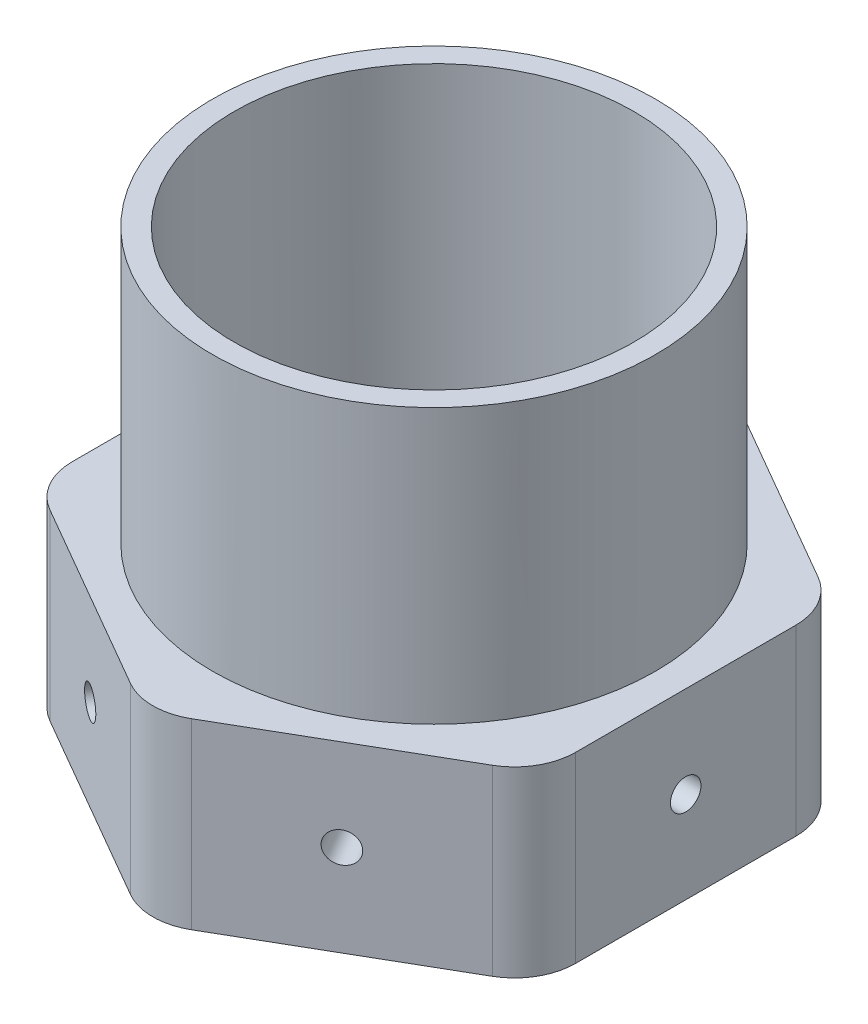
SolidWorks part; units mm, degrees
ref_plane "Front Plane" through (0, 0, 0) normal (0, 0, 1) x (1, 0, 0)
ref_plane "Top Plane" through (0, 0, 0) normal (0, 1, 0) x (1, 0, 0)
ref_plane "Right Plane" through (0, 0, 0) normal (1, 0, 0) x (0, 0, -1)
sketch "Sketch1" plane through (0, 0, 0) normal (0, 1, 0) x (1, 0, 0)
  line L9 (0, -60.5652) -> (52.451, -30.2826)
  line L10 (52.451, -30.2826) -> (52.451, 30.2826)
  line L11 (52.451, 30.2826) -> (0, 60.5652)
  line L12 (0, 60.5652) -> (-52.451, 30.2826)
  line L13 (-52.451, 30.2826) -> (-52.451, -30.2826)
  line L14 (-52.451, -30.2826) -> (0, -60.5652)
  circle A0 centre (0, 0) radius 41.656
  circle A1 centre (0, 0) radius 52.451 construction
  dimension "D1" = 10.795
  dimension "D2" = 83.312
extrude "Boss-Extrude1" add sketch "Sketch1" along normal blind 38.1
sketch "Sketch2" plane through (-52.451, 0, 0) normal (-1, 0, 0) x (0, 0, 1)
  circle A0 centre (0, 19.05) radius 3.1813
  dimension "D1" = 6.3627
extrude "Cut-Extrude1" cut sketch "Sketch2" against normal blind 29.464 contours A0
pattern_circular "CirPattern1" count 6 over 360 about axis through (0, 38.1, 0) along (0, 1, 0) of "Cut-Extrude1"
ref_plane "Plane1" through (-52.451, 38.1, -30.2826) normal (0, -1, 0) x (-1, 0, 0)
sketch "Sketch3" plane through (-52.451, 38.1, -30.2826) normal (0, -1, 0) x (1, 0, 0)
  circle A0 centre (52.451, 30.2826) radius 41.656
  circle A1 centre (52.451, 30.2826) radius 46.1518
  circle A2 centre (52.451, 30.2826) radius 41.656 construction
  circle A3 centre (52.451, 30.2826) radius 41.656 construction
  dimension "D1" = 4.4958
extrude "Boss-Extrude2" add sketch "Sketch3" against normal blind 57.15
fillet "Fillet1" radius 12.7 6 edges at (-52.451, 19.05, -30.2826) (0, 19.05, -60.5652) (52.451, 19.05, -30.2826) (52.451, 19.05, 30.2826) (-52.451, 19.05, 30.2826) (0, 19.05, 60.5652)
